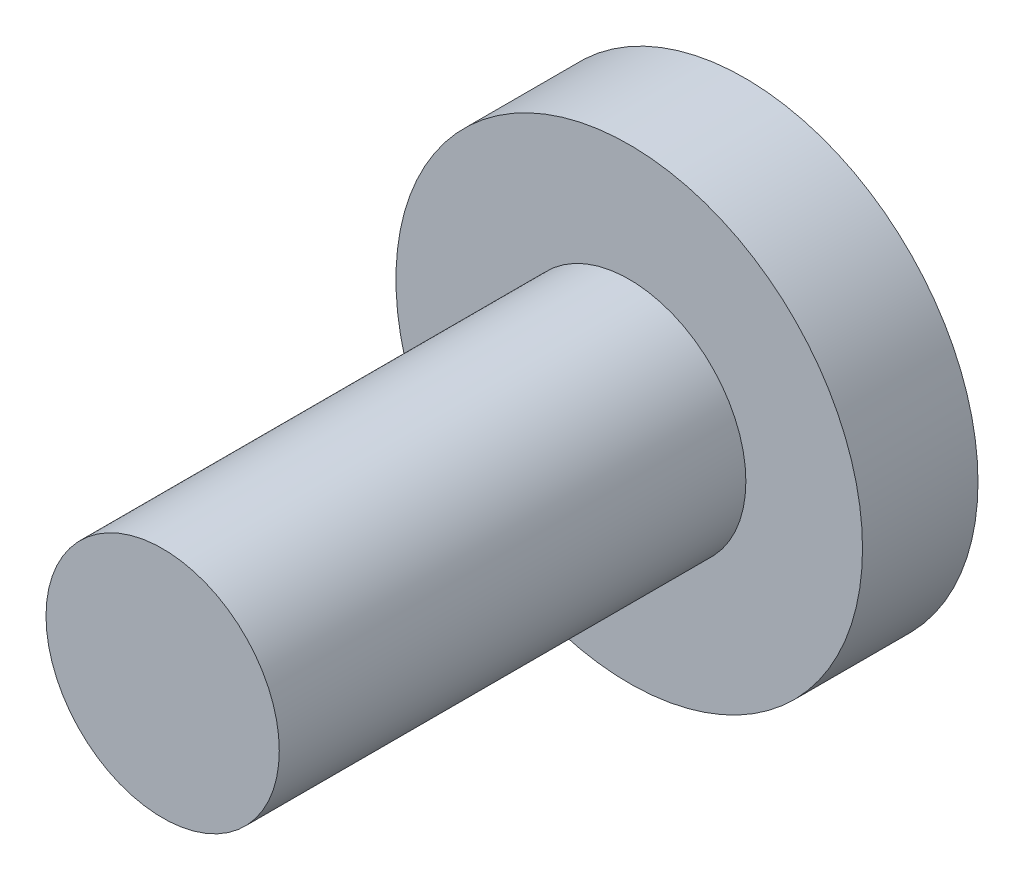
SolidWorks part; units mm, degrees
ref_plane "Front Plane" through (0, 0, 0) normal (0, 0, 1) x (1, 0, 0)
ref_plane "Top Plane" through (0, 0, 0) normal (0, 1, 0) x (1, 0, 0)
ref_plane "Right Plane" through (0, 0, 0) normal (1, 0, 0) x (0, 0, -1)
sketch "Sketch1" plane through (0, 0, 0) normal (0, 0, 1) x (1, 0, 0)
  circle A0 centre (0, 0) radius 101.6
  dimension "D1" = 203.2
extrude "Boss-Extrude1" add sketch "Sketch1" along normal blind 50.292
sketch "Sketch2" plane through (0, 0, 50.292) normal (0, 0, 1) x (1, 0, 0)
  circle A0 centre (0, 0) radius 50.8
  dimension "D1" = 101.6
extrude "Boss-Extrude2" add sketch "Sketch2" along normal blind 203.2
